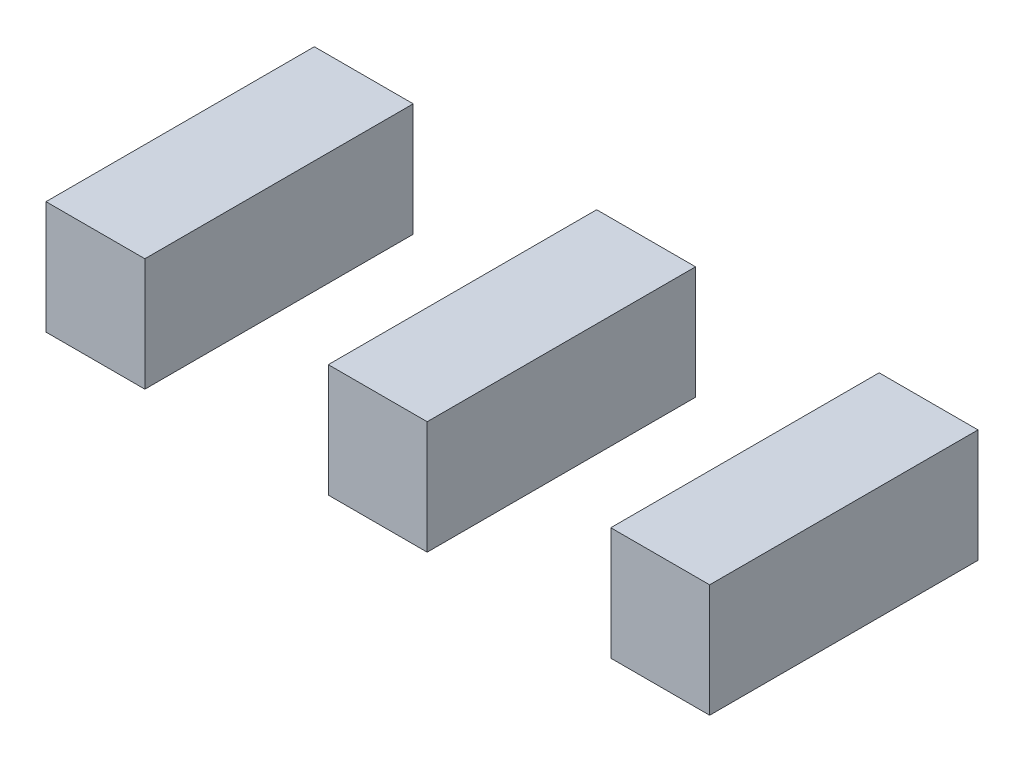
SolidWorks part; units mm, degrees
ref_plane "Front Plane" through (0, 0, 0) normal (0, 0, 1) x (1, 0, 0)
ref_plane "Top Plane" through (0, 0, 0) normal (0, 1, 0) x (1, 0, 0)
ref_plane "Right Plane" through (0, 0, 0) normal (1, 0, 0) x (0, 0, -1)
sketch "Sketch1" plane through (0, 0, 0) normal (0, 1, 0) x (1, 0, 0)
  line L1 (3.5, 9.5) -> (-3.5, 9.5)
  line L2 (3.5, 9.5) -> (3.5, -9.5)
  line L3 (3.5, -9.5) -> (-3.5, -9.5)
  line L4 (-3.5, 9.5) -> (-3.5, -9.5)
  line L5 (3.5, 9.5) -> (-3.5, -9.5) construction
  line L6 (3.5, -9.5) -> (-3.5, 9.5) construction
  line L7 (16.5, 9.5) -> (23.5, 9.5)
  line L8 (16.5, 9.5) -> (16.5, -9.5)
  line L9 (16.5, -9.5) -> (23.5, -9.5)
  line L10 (23.5, 9.5) -> (23.5, -9.5)
  line L11 (16.5, 9.5) -> (23.5, -9.5) construction
  line L12 (16.5, -9.5) -> (23.5, 9.5) construction
  line L13 (-16.4878, 9.5) -> (-23.4878, 9.5)
  line L14 (-16.4878, 9.5) -> (-16.4878, -9.5)
  line L15 (-16.4878, -9.5) -> (-23.4878, -9.5)
  line L16 (-23.4878, 9.5) -> (-23.4878, -9.5)
  line L17 (-16.4878, 9.5) -> (-23.4878, -9.5) construction
  line L18 (-16.4878, -9.5) -> (-23.4878, 9.5) construction
  point P0 (0, 0)
  point P6 (20, 0)
  point P11 (-19.9878, 0)
  dimension "D1" = 7
  dimension "D2" = 19
  dimension "D3" = 19
  dimension "D4" = 7
  dimension "D5" = 20
  dimension "D6" = 7
  dimension "D7" = 19
  dimension "D8" = 19.9878
extrude "Boss-Extrude1" add sketch "Sketch1" along normal blind 8
